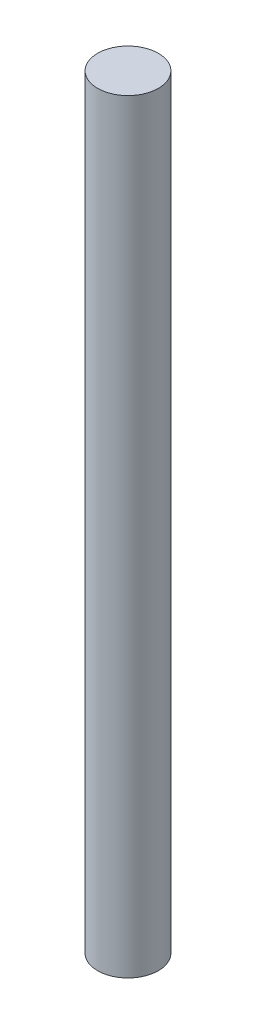
SolidWorks part; units mm, degrees
ref_plane "前视基准面" through (0, 0, 0) normal (0, 0, 1) x (1, 0, 0)
ref_plane "上视基准面" through (0, 0, 0) normal (0, 1, 0) x (1, 0, 0)
ref_plane "右视基准面" through (0, 0, 0) normal (1, 0, 0) x (0, 0, -1)
sketch "草图1" plane through (0, 0, 0) normal (0, 1, 0) x (1, 0, 0)
  circle A0 centre (0, -0.4565) radius 2.5
  dimension "D1" = 5
extrude "凸台-拉伸1" add sketch "草图1" along normal blind 62.9
